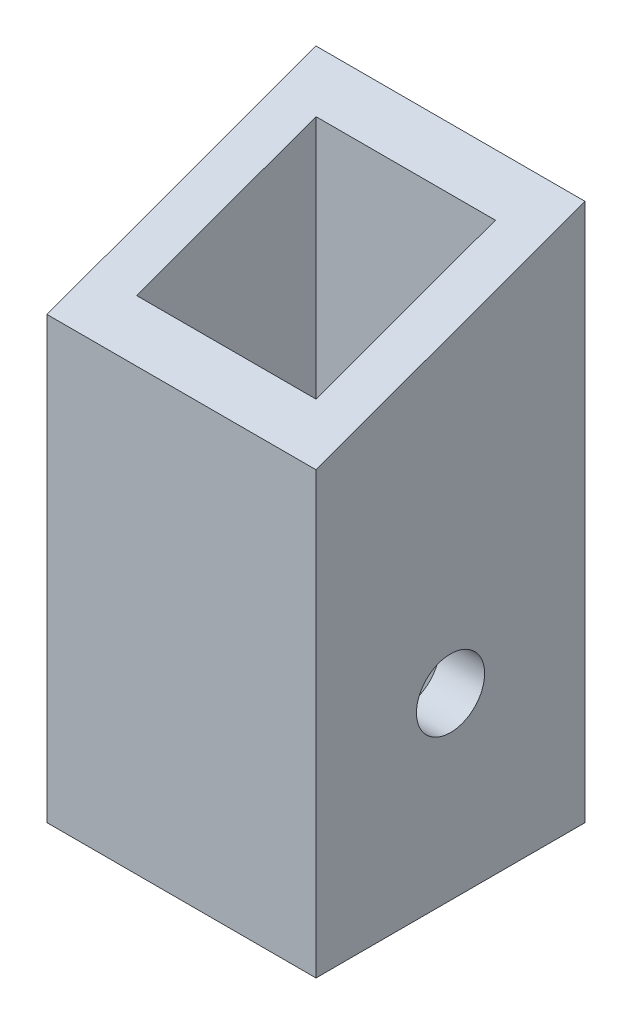
SolidWorks part; units mm, degrees
material "6061 Alloy"
ref_plane "Front Plane" through (0, 0, 0) normal (0, 0, 1) x (1, 0, 0)
ref_plane "Top Plane" through (0, 0, 0) normal (0, 1, 0) x (1, 0, 0)
ref_plane "Right Plane" through (0, 0, 0) normal (1, 0, 0) x (0, 0, -1)
sketch "Sketch1" plane through (0, 0, 0) normal (1, 0, 0) x (0, 0, -1)
  line L4 (268.4949, -191.8078) -> (268.4949, -229.9078) construction
  line L5 (268.4949, -229.9078) -> (249.4449, -229.9078) construction
  line L6 (249.4449, -229.9078) -> (249.4449, -198.7415) construction
  line L7 (249.4449, -198.7415) -> (268.4949, -191.8078) construction
  line L18 (268.4949, -191.8078) -> (268.4949, -229.9078)
  line L19 (268.4949, -229.9078) -> (249.4449, -229.9078)
  line L20 (249.4449, -229.9078) -> (249.4449, -198.7415)
  line L21 (249.4449, -198.7415) -> (268.4949, -191.8078)
extrude "Boss-Extrude1" add sketch "Sketch1" along normal blind 19.05
sketch "Sketch2" plane through (0, -229.9078, 0) normal (0, -1, 0) x (1, 0, 0)
  line L0 (19.05, -268.4949) -> (0, -268.4949) construction
  line L1 (3.175, -252.6199) -> (15.875, -252.6199)
  line L2 (3.175, -252.6199) -> (3.175, -265.3199)
  line L3 (3.175, -265.3199) -> (15.875, -265.3199)
  line L4 (15.875, -252.6199) -> (15.875, -265.3199)
  line L5 (3.175, -252.6199) -> (15.875, -265.3199) construction
  line L6 (3.175, -265.3199) -> (15.875, -252.6199) construction
  line L7 (19.05, -249.4449) -> (19.05, -268.4949) construction
  line L8 (19.05, -249.4449) -> (0, -249.4449) construction
  line L9 (0, -249.4449) -> (0, -268.4949) construction
  point P0 (9.525, -258.9699)
  dimension "D1" = 3.175
  dimension "D2" = 3.175
  dimension "D3" = 3.175
  dimension "D4" = 3.175
extrude "Cut-Extrude1" cut sketch "Sketch2" against normal through all
sketch "Sketch3" plane through (19.05, 0, 0) normal (1, 0, 0) x (0, 0, -1)
  line L0 (268.4949, -229.9078) -> (268.4949, -191.8078) construction
  line L1 (249.4449, -229.9078) -> (268.4949, -229.9078) construction
  circle A0 centre (258.9699, -217.2078) radius 2.413
  dimension "D1" = 4.826
  dimension "D2" = 9.525
  dimension "D3" = 12.7
extrude "Cut-Extrude2" cut sketch "Sketch3" against normal through all
